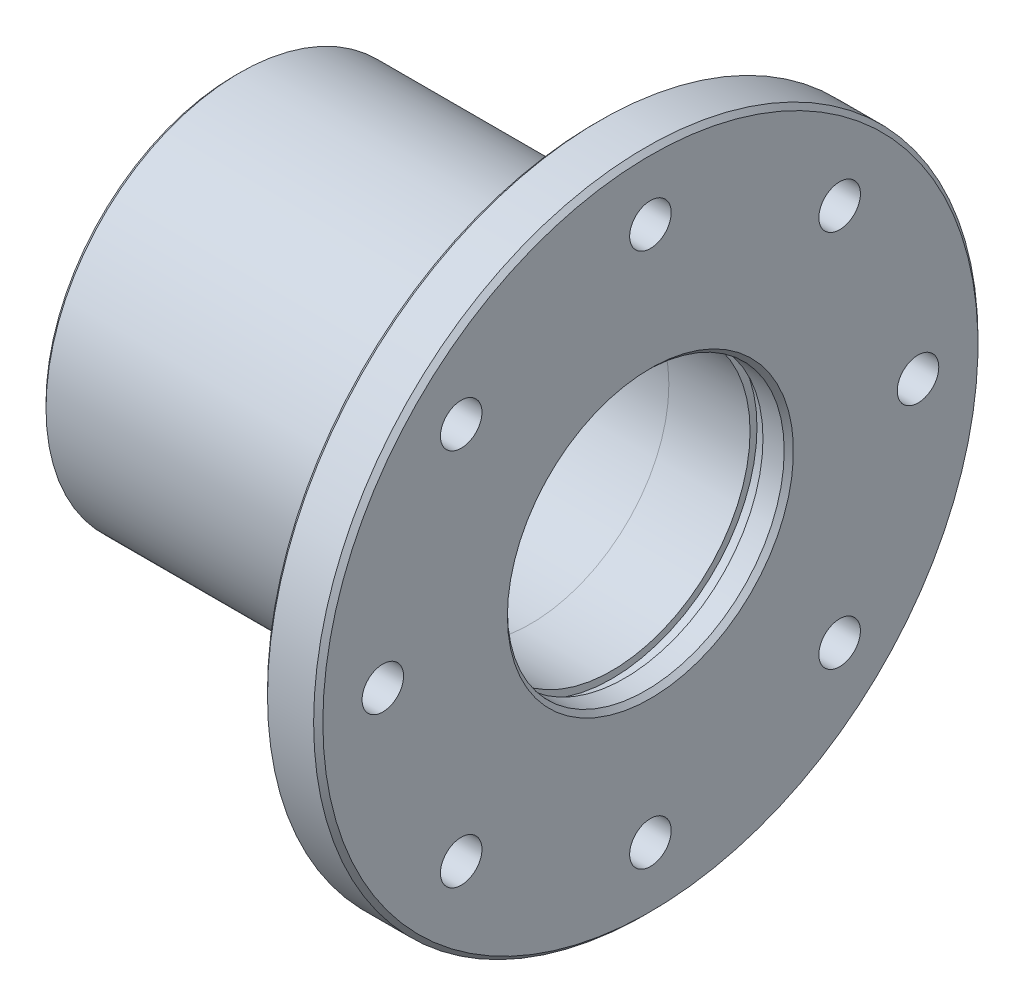
SolidWorks part; units mm, degrees
material "Сталь 45 ГОСТ 1050-88"
ref_plane "Front Plane" through (0, 0, 0) normal (0, 0, 1) x (1, 0, 0)
ref_plane "Top Plane" through (0, 0, 0) normal (0, 1, 0) x (1, 0, 0)
ref_plane "Right Plane" through (0, 0, 0) normal (1, 0, 0) x (0, 0, -1)
sketch "Skizze2" plane through (0, 0, 0) normal (0, 1, 0) x (1, 0, 0)
  line L0 (0, 0) -> (0, 15.5)
  line L1 (0, 0) -> (0, -15)
  line L2 (0, 0) -> (0, -25)
  line L3 (0, 15.5) -> (0, 20.5021)
  line L4 (0.5, 21.0021) -> (38.5, 21.0021)
  line L5 (45, 20) -> (45, 15.5)
  line L6 (45, -25) -> (0, -25)
  line L7 (0.5, 15) -> (2.8, 15)
  line L8 (33.5, -25) -> (33.5, 25) construction
  line L9 (0, 0) -> (70.091, 0)
  line L10 (0.5, 15) -> (2.8, 15)
  line L11 (2.8, 15) -> (2.8, 15.75)
  line L12 (2.8, 15.75) -> (4.2, 15.75)
  line L13 (4.2, 15.75) -> (4.2, 15)
  line L14 (4.2, 15) -> (40.8, 15)
  line L16 (45, -15) -> (42.2, -15)
  line L17 (45, -15) -> (42.2, -15)
  line L18 (42.2, -15) -> (42.2, -15.75)
  line L21 (42.2, -15.75) -> (40.8, -15.75)
  line L22 (40.8, -15.75) -> (40.8, -15)
  line L23 (40.8, 15.75) -> (40.8, 15)
  line L25 (4.2, -15) -> (40.8, -15)
  line L26 (4.2, -15.75) -> (4.2, -15)
  line L27 (2.8, -15.75) -> (4.2, -15.75)
  line L28 (2.8, -15) -> (2.8, -15.75)
  line L29 (0, -15) -> (2.8, -15)
  line L30 (0, -15) -> (2.8, -15)
  line L31 (42.2, 15.75) -> (40.8, 15.75)
  line L32 (42.2, 15) -> (42.2, 15.75)
  line L33 (44.5, 15) -> (42.2, 15)
  line L34 (44.5, 15) -> (42.2, 15)
  line L35 (45, 0) -> (45, -25)
  line L36 (45, 0) -> (45, -15)
  line L37 (45, 0) -> (45, 15.5)
  line L38 (42.2, -15) -> (45, -15)
  line L39 (42.2, 15) -> (44.5, 15)
  line L40 (42.2, 15) -> (44.5, 15)
  line L44 (45, 20) -> (45, 35.5)
  line L45 (44.5, 36) -> (39.5, 36)
  line L46 (39, 35.5) -> (39, 21.5021)
  line L47 (42.2, -15) -> (45, -15)
  line L48 (45, 15.5) -> (44.5, 15)
  line L49 (45, 35.5) -> (44.5, 36)
  line L50 (39.5, 36) -> (39, 35.5)
  line L51 (0, 15.5) -> (0.5, 15)
  line L52 (0, 20.5021) -> (0.5, 21.0021)
  arc A0 (38.5, 21.0021) -> (39, 21.5021) centre (38.5, 21.5021) ccw
  point P6 (0, 21.0021)
  point P33 (39, 36)
  point P35 (45, 36)
  point P46 (19.2125, 21.0021)
revolve "Rotation1" add sketch "Skizze2" angle 360 about L9
sketch "Skizze3" plane through (45, 0, 0) normal (1, 0, 0) x (0, 0, -1)
  circle A0 centre (0, 0) radius 20
  point P3 (0, 20)
  point P6 (14.1421, 14.1421)
  point P7 (20, 0)
  point P8 (14.1421, -14.1421)
  point P9 (0, -20)
  point P10 (-14.1421, -14.1421)
  point P11 (-20, 0)
  point P12 (-14.1421, 14.1421)
  point P13 (0, 0)
  dimension "D1" = 8
hole_wizard "M4 Gewindebohrung1" positions "3D-Skizze1" profile "Skizze4" tap size "M4" standard "DIN"
sketch3d "3D-Skizze1"
  point P0 (67, 14.1421, 14.1421)
  point P3 (67, 20, 0)
  point P6 (67, 14.1421, -14.1421)
  point P9 (67, 0, -20)
  point P12 (67, -14.1421, -14.1421)
  point P15 (67, -20, 0)
  point P18 (67, -14.1421, 14.1421)
  point P21 (67, 0, 20)
sketch "Skizze4" plane through (67, 14.1421, 14.1421) normal (0, 1, 0) x (0, 0, -1)
  line L0 (0, 0) -> (0, 13.9914)
  line L1 (0, 13.9914) -> (1.65, 13)
  line L2 (1.65, 13) -> (1.65, 0)
  line L5 (1.65, 0) -> (0, 0)
  line L10 (0, 13.9914) -> (-1.65, 13) construction
  line L11 (0, -6.35) -> (0, 107.95) construction
  dimension "Bohrerdurchmesser" = 3.3
  dimension "Bohrungstiefe" = 13
  dimension "Spitzenwinkel" = 118
cosmetic thread "Bohrungsgewinde1" [suppressed] parameters "D1"=8, "D2"=4
cosmetic thread "Bohrungsgewinde2" [suppressed] parameters "D1"=8, "D2"=4
cosmetic thread "Bohrungsgewinde3" [suppressed] parameters "D1"=8, "D2"=4
cosmetic thread "Bohrungsgewinde4" [suppressed] parameters "D1"=8, "D2"=4
cosmetic thread "Bohrungsgewinde5" [suppressed] parameters "D1"=8, "D2"=4
cosmetic thread "Bohrungsgewinde6" [suppressed] parameters "D1"=8, "D2"=4
cosmetic thread "Bohrungsgewinde7" [suppressed] parameters "D1"=8, "D2"=4
cosmetic thread "Bohrungsgewinde8" [suppressed] parameters "D1"=8, "D2"=4
sketch "Skizze5" plane through (0, 0, 0) normal (-1, 0, 0) x (0, 0, 1)
  line L0 (0, 0) -> (0, 20)
  line L1 (0, 0) -> (0, -20)
  line L2 (0, -20) -> (-7.5, -20)
  line L3 (0, -20) -> (7.5, -20)
  line L4 (7.5, -20) -> (7.5, 20)
  line L5 (-7.5, -20) -> (-7.5, 20)
  line L6 (-7.5, 20) -> (7.5, 20)
  circle A1 centre (0, 0) radius 20
  point P9 (7.5, 18.5405)
  point P10 (-7.5, 20)
  point P11 (7.5, 18.5405)
  point P12 (7.5, 18.5405)
  point P13 (7.5, 18.5405)
  point P16 (-7.5, 18.5405)
  point P17 (-7.5, 18.5405)
  point P18 (7.5, 18.5405)
  point P19 (-7.5, -18.5405)
  point P20 (7.5, -18.5405)
  point P21 (7.5, -18.5405)
  point P22 (-7.5, -18.5405)
  point P23 (7.5, -18.5405)
sketch "Skizze7" plane through (0, 0, 0) normal (0, 1, 0) x (1, 0, 0)
  line L0 (45, -35.5) -> (45, 35.5) construction
  line L2 (45, -35.5) -> (45, 35.5)
  line L10 (32, 25) -> (32, -25)
  line L13 (13, 25) -> (13, -25)
split line "Trennlinie1"
fillet "Verrundung1" [suppressed] radius 0.5
sketch "Skizze8" plane through (45, 0, 0) normal (1, 0, 0) x (0, 0, -1)
  circle A0 centre (0, 0) radius 29
  circle A1 centre (0, 29) radius 2.25
  circle A2 centre (20.5061, 20.5061) radius 2.25
  circle A3 centre (29, 0) radius 2.25
  circle A4 centre (20.5061, -20.5061) radius 2.25
  circle A5 centre (0, -29) radius 2.25
  circle A6 centre (-20.5061, -20.5061) radius 2.25
  circle A7 centre (-29, 0) radius 2.25
  circle A8 centre (-20.5061, 20.5061) radius 2.25
  point P3 (0, 29)
  point P6 (20.5061, 20.5061)
  point P7 (29, 0)
  point P8 (20.5061, -20.5061)
  point P9 (0, -29)
  point P10 (-20.5061, -20.5061)
  point P11 (-29, 0)
  point P12 (-20.5061, 20.5061)
  point P13 (0, 0)
  point P30 (0, 0)
  dimension "D1" = 8
  dimension "D2" = 8
extrude "Schnitt-Linear austragen1" cut sketch "Skizze8" against normal through all contours A0 A8 | A0 A8 | A0 A1 | A0 A1 | A0 A2 | A0 A2 | A0 A3 | A0 A3 | A0 A4 | A0 A4 | A0 A5 | A0 A5 | A0 A6 | A0 A6 | A0 A7 | A0 A7
